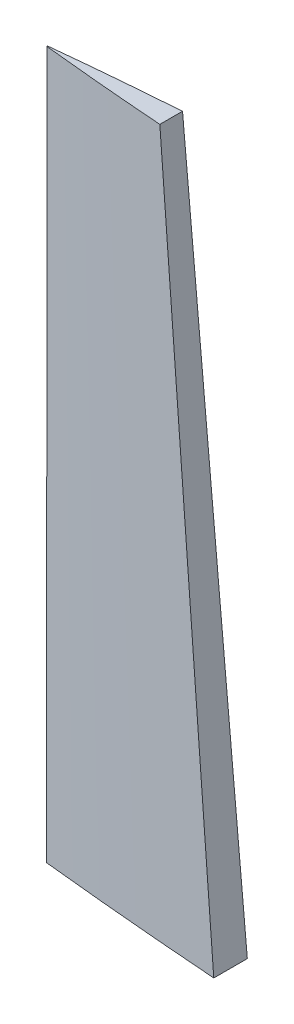
SolidWorks part; units mm, degrees
ref_plane "Front Plane" through (0, 0, 0) normal (0, 0, 1) x (1, 0, 0)
ref_plane "Top Plane" through (0, 0, 0) normal (0, 1, 0) x (1, 0, 0)
ref_plane "Right Plane" through (0, 0, 0) normal (1, 0, 0) x (0, 0, -1)
ref_plane "Plane1" through (0, 22, 0) normal (0, 1, 0) x (1, 0, 0)
sketch "Sketch1" plane through (0, 22, 0) normal (0, 1, 0) x (1, 0, 0)
  line L0 (-113.6268, 4.2175) -> (-113.6268, -4.2175)
  line L1 (-159.684, 0.1451) -> (-159.684, -0.1451)
  spline S0 degree 3 poles (-113.6268, 4.2175) (-113.7992, 4.2053) (-116.3588, 4.0247) (-121.1639, 3.6526) (-127.878, 3.1166) (-134.0992, 2.5902) (-139.7598, 2.0899) (-144.7977, 1.626) (-149.1576, 1.2099) (-152.7919, 0.8522) (-155.6606, 0.5626) (-157.7325, 0.3492) (-158.9847, 0.2186) (-159.5438, 0.1598) (-159.684, 0.1451) knots 0 0 0 0 0.011212 0.166483 0.312686 0.448211 0.571563 0.681381 0.776452 0.855723 0.918312 0.963525 0.990856 1 1 1 1
  spline S1 degree 3 poles (-113.6268, -4.2175) (-113.7992, -4.2053) (-116.3588, -4.0247) (-121.1639, -3.6526) (-127.878, -3.1166) (-134.0992, -2.5902) (-139.7598, -2.0899) (-144.7977, -1.626) (-149.1576, -1.2099) (-152.7919, -0.8522) (-155.6606, -0.5626) (-157.7325, -0.3492) (-158.9847, -0.2186) (-159.5438, -0.1598) (-159.684, -0.1451) knots 0 0 0 0 0.011212 0.166483 0.312686 0.448211 0.571563 0.681381 0.776452 0.855723 0.918312 0.963525 0.990856 1 1 1 1
ref_plane "Plane2" through (0, 199.605, 0) normal (0, 1, 0) x (1, 0, 0)
sketch "Sketch2" plane through (0, 199.605, 0) normal (0, 1, 0) x (1, 0, 0)
  line L0 (-128.5456, 2.8514) -> (-128.5456, -2.8514)
  line L1 (-159.684, 0.0981) -> (-159.684, -0.0981)
  spline S0 degree 3 poles (-128.5456, 2.8514) (-128.6622, 2.8431) (-130.3927, 2.721) (-133.6413, 2.4694) (-138.1805, 2.107) (-142.3866, 1.7512) (-146.2137, 1.4129) (-149.6197, 1.0993) (-152.5673, 0.818) (-155.0244, 0.5761) (-156.9639, 0.3803) (-158.3646, 0.2361) (-159.2112, 0.1478) (-159.5892, 0.108) (-159.684, 0.0981) knots 0 0 0 0 0.011212 0.166483 0.312686 0.448211 0.571563 0.681381 0.776452 0.855723 0.918312 0.963525 0.990856 1 1 1 1
  spline S1 degree 3 poles (-128.5456, -2.8514) (-128.6622, -2.8431) (-130.3927, -2.721) (-133.6413, -2.4694) (-138.1805, -2.107) (-142.3866, -1.7512) (-146.2137, -1.4129) (-149.6197, -1.0993) (-152.5673, -0.818) (-155.0244, -0.5761) (-156.9639, -0.3803) (-158.3646, -0.2361) (-159.2112, -0.1478) (-159.5892, -0.108) (-159.684, -0.0981) knots 0 0 0 0 0.011212 0.166483 0.312686 0.448211 0.571563 0.681381 0.776452 0.855723 0.918312 0.963525 0.990856 1 1 1 1
loft "Loft1" add profiles "Sketch1", "Sketch2"
